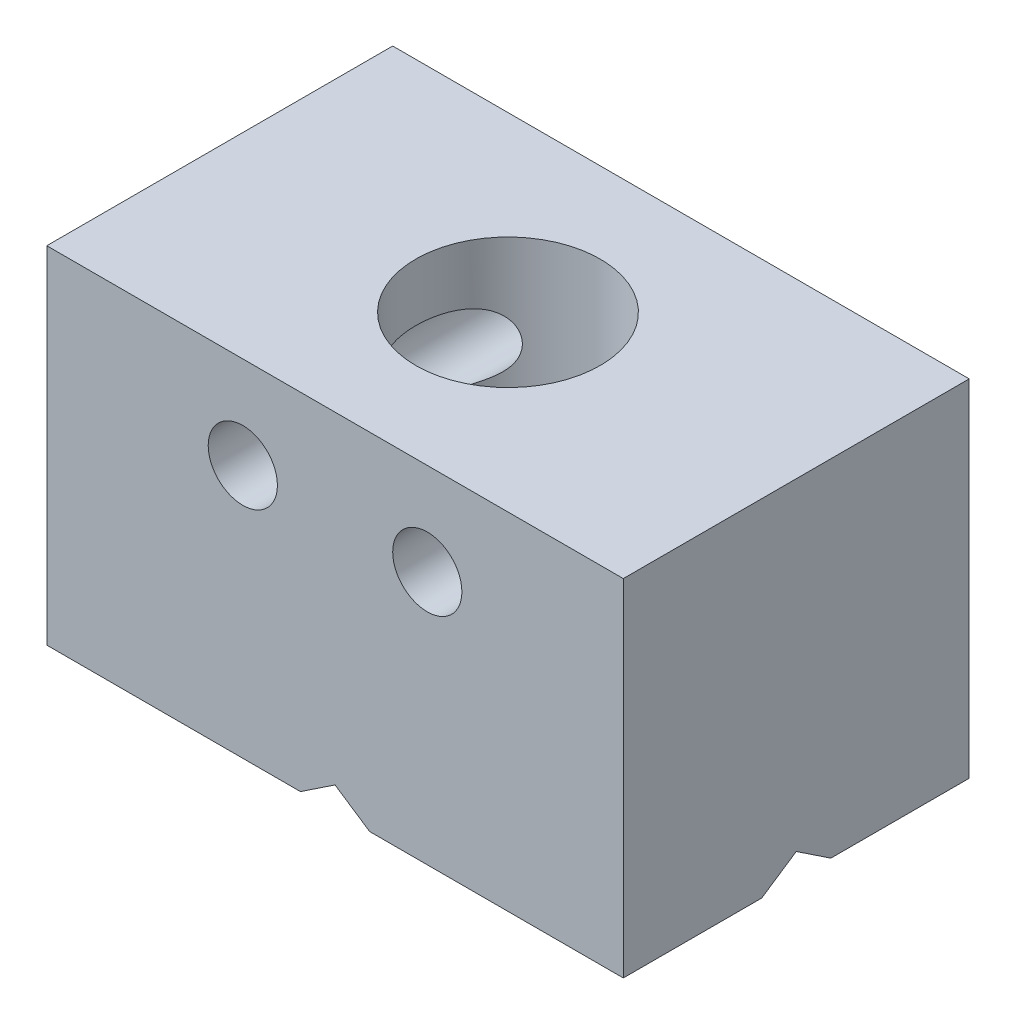
SolidWorks part; units mm, degrees
ref_plane "Front Plane" through (0, 0, 0) normal (0, 0, 1) x (1, 0, 0)
ref_plane "Top Plane" through (0, 0, 0) normal (0, 1, 0) x (1, 0, 0)
ref_plane "Right Plane" through (0, 0, 0) normal (1, 0, 0) x (0, 0, -1)
sketch "Sketch1" plane through (0, 0, 0) normal (0, 0, 1) x (1, 0, 0)
  line L1 (12.5, -7.5) -> (-12.5, -7.5)
  line L2 (12.5, -7.5) -> (12.5, 7.5)
  line L3 (12.5, 7.5) -> (-12.5, 7.5)
  line L4 (-12.5, -7.5) -> (-12.5, 7.5)
  line L5 (12.5, -7.5) -> (-12.5, 7.5) construction
  line L6 (12.5, 7.5) -> (-12.5, -7.5) construction
  point P0 (0, 0)
  dimension "D1" = 25
  dimension "D2" = 15
extrude "Boss-Extrude1" add sketch "Sketch1" along normal blind 15
hole_wizard "Ø3.0mm Dowel Hole1" positions "Sketch2" profile "Sketch3" hole size "Ø3.0" standard "ISO" end condition up to next
sketch "Sketch2" plane through (0, 0, 0) normal (0, 0, -1) x (-1, 0, 0)
  line L0 (12.5, -7.5) -> (-12.5, -7.5) construction
  point P0 (4, 3.5)
  point P2 (-4, 3.5)
  dimension "D1" = 8
  dimension "D2" = 0
  dimension "D3" = 11
  dimension "D4" = 4
sketch "Sketch3" plane through (-4, 3.5, 0) normal (1, 0, 0) x (0, 1, 0)
  line L0 (0, 0) -> (0, 15)
  line L1 (0, 15) -> (1.5, 15)
  line L2 (1.5, 15) -> (1.5, 0)
  line L5 (1.5, 0) -> (0, 0)
  line L11 (0, -6.35) -> (0, 107.95) construction
  dimension "Thru Hole Dia." = 3
  dimension "Thru Hole Depth" = 15
sketch "Sketch4" plane through (0, 0, 0) normal (0, 0, -1) x (-1, 0, 0)
  line L0 (-1.5, -7.5) -> (0, -6.5)
  line L1 (12.5, -7.5) -> (-12.5, -7.5) construction
  line L2 (0, -6.5) -> (1.5, -7.5)
  line L3 (-1.5, -7.5) -> (-1.5, -8.6619)
  line L4 (-1.5, -8.6619) -> (1.5, -8.6619)
  line L5 (1.5, -8.6619) -> (1.5, -7.5)
  dimension "D1" = 3
  dimension "D2" = 1.5
  dimension "D3" = 1
extrude "Cut-Extrude1" cut sketch "Sketch4" against normal blind 15
sketch "Sketch5" plane through (-12.5, 0, 0) normal (-1, 0, 0) x (0, 0, 1)
  line L0 (6, -7.5) -> (7.5, -6.5)
  line L1 (15, -7.5) -> (0, -7.5) construction
  line L2 (7.5, -6.5) -> (9, -7.5)
  line L3 (15, 7.5) -> (0, 7.5) construction
  line L4 (6, -7.5) -> (6.1405, -8.4975)
  line L5 (6.1405, -8.4975) -> (9, -8.4975)
  line L6 (9, -8.4975) -> (9, -7.5)
  point P7 (7.5, 7.5)
  point P8 (7.5, -7.5)
  dimension "D1" = 3
  dimension "D2" = 1.5
  dimension "D3" = 1
extrude "Cut-Extrude2" cut sketch "Sketch5" against normal blind 49
hole_wizard "Ø8.0mm Dowel Hole1" positions "Sketch6" profile "Sketch7" hole size "Ø8.0" standard "ISO"
sketch "Sketch6" plane through (0, 7.5, 0) normal (0, 1, 0) x (1, 0, 0)
  point P0 (0, -7.5)
  dimension "D1" = 7.5
  dimension "D2" = 12.5
sketch "Sketch7" plane through (0, 7.5, 7.5) normal (1, 0, 0) x (0, 0, 1)
  line L0 (0, 0) -> (0, 11.4034)
  line L1 (0, 11.4034) -> (4, 9)
  line L2 (4, 9) -> (4, 0)
  line L5 (4, 0) -> (0, 0)
  line L10 (0, 11.4034) -> (-4, 9) construction
  line L11 (0, -6.35) -> (0, 107.95) construction
  dimension "Hole Dia." = 8
  dimension "Hole Depth" = 9
  dimension "Drill Angle" = 118
